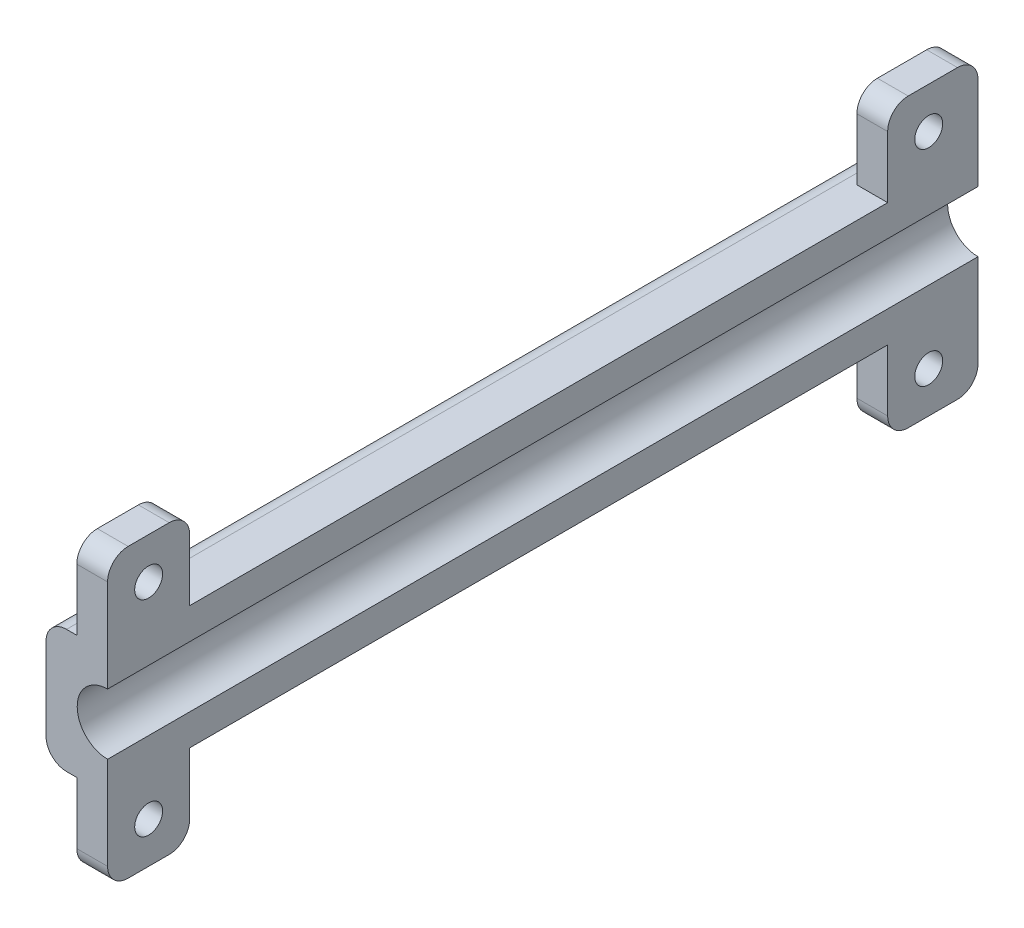
SolidWorks part; units mm, degrees
ref_plane "Front Plane" through (0, 0, 0) normal (0, 0, 1) x (1, 0, 0)
ref_plane "Top Plane" through (0, 0, 0) normal (0, 1, 0) x (1, 0, 0)
ref_plane "Right Plane" through (0, 0, 0) normal (1, 0, 0) x (0, 0, -1)
sketch "Sketch2" plane through (0, 0, 0) normal (0, 0, 1) x (1, 0, 0)
  line L0 (2.75, 15) -> (2.75, 0)
  line L1 (-4.75, 0) -> (10.25, 0)
  line L2 (-4.75, 0) -> (-4.75, 15)
  line L3 (-4.75, 15) -> (10.25, 15)
  line L4 (10.25, 0) -> (10.25, 15)
  line L5 (-4.75, 0) -> (10.25, 15) construction
  line L6 (-4.75, 15) -> (10.25, 0) construction
  circle A0 centre (2.75, 7.5) radius 3.7
  point P0 (2.75, 7.5)
  line M5 (2.75, 3.8) -> (2.75, -7.5)
  line M13 (2.75, 22.5) -> (2.75, 11.2)
extrude "Boss-Extrude1" add sketch "Sketch2" against normal up to surface (106 mm away) contours A0 L3 L2 L1 M13 M5
sketch "Sketch3" plane through (2.75, 0, 0) normal (-1, 0, 0) x (0, 0, 1)
  line L8 (-106, 3.8) -> (-106, -7.5)
  line L9 (-103.5, -10) -> (-97.5, -10)
  line L10 (-95, -7.5) -> (-95, 0)
  line L11 (-95, 0) -> (-10, 0)
  line L12 (-10, 0) -> (-10, -7.5)
  line L13 (-7.5, -10) -> (-2.5, -10)
  line L14 (0, -7.5) -> (0, 3.8)
  line L15 (0, 3.8) -> (-106, 3.8)
  line L17 (-103.5, -10) -> (-97.5, -10)
  line L18 (-95, -7.5) -> (-95, 0)
  line L19 (-95, 0) -> (-10, 0)
  line L20 (-10, 0) -> (-10, -7.5)
  line L21 (-7.5, -10) -> (-2.5, -10)
  line L22 (0, -7.5) -> (0, 3.8)
  line L23 (0, 3.8) -> (-106, 3.8)
  line L24 (-106, 11.2) -> (0, 11.2)
  line L25 (0, 11.2) -> (0, 22.5)
  line L26 (-2.5, 25) -> (-7.5, 25)
  line L27 (-10, 22.5) -> (-10, 15)
  line L28 (-10, 15) -> (-95, 15)
  line L29 (-95, 15) -> (-95, 22.5)
  line L30 (-97.5, 25) -> (-103.5, 25)
  line L31 (-106, 22.5) -> (-106, 11.2)
  line L32 (-106, 11.2) -> (0, 11.2)
  line L33 (0, 11.2) -> (0, 22.5)
  line L34 (-2.5, 25) -> (-7.5, 25)
  line L35 (-10, 22.5) -> (-10, 15)
  line L36 (-10, 15) -> (-95, 15)
  line L37 (-95, 15) -> (-95, 22.5)
  line L38 (-97.5, 25) -> (-103.5, 25)
  line L48 (-106, 3.8) -> (-106, -7.5)
  line L49 (-106, 22.5) -> (-106, 11.2)
  circle A0 centre (-100, 20) radius 1.7 construction
  circle A1 centre (-5, 20) radius 1.7 construction
  circle A2 centre (-5, -5) radius 1.7 construction
  circle A3 centre (-100, -5) radius 1.7 construction
  circle A4 centre (-5, 20) radius 1.7
  circle A5 centre (-5, -5) radius 1.7
  circle A6 centre (-100, -5) radius 1.7
  circle A7 centre (-100, 20) radius 1.7
  arc A16 (-106, -7.5) -> (-103.5, -10) centre (-103.5, -7.5) ccw
  arc A17 (-106, -7.5) -> (-103.5, -10) centre (-103.5, -7.5) ccw
  arc A18 (-97.5, -10) -> (-95, -7.5) centre (-97.5, -7.5) ccw
  arc A19 (-97.5, -10) -> (-95, -7.5) centre (-97.5, -7.5) ccw
  arc A20 (-10, -7.5) -> (-7.5, -10) centre (-7.5, -7.5) ccw
  arc A21 (-10, -7.5) -> (-7.5, -10) centre (-7.5, -7.5) ccw
  arc A22 (-2.5, -10) -> (0, -7.5) centre (-2.5, -7.5) ccw
  arc A23 (-2.5, -10) -> (0, -7.5) centre (-2.5, -7.5) ccw
  arc A24 (-103.5, 25) -> (-106, 22.5) centre (-103.5, 22.5) ccw
  arc A25 (-103.5, 25) -> (-106, 22.5) centre (-103.5, 22.5) ccw
  arc A26 (0, 22.5) -> (-2.5, 25) centre (-2.5, 22.5) ccw
  arc A27 (0, 22.5) -> (-2.5, 25) centre (-2.5, 22.5) ccw
  arc A28 (-7.5, 25) -> (-10, 22.5) centre (-7.5, 22.5) ccw
  arc A29 (-7.5, 25) -> (-10, 22.5) centre (-7.5, 22.5) ccw
  arc A30 (-95, 22.5) -> (-97.5, 25) centre (-97.5, 22.5) ccw
  arc A31 (-95, 22.5) -> (-97.5, 25) centre (-97.5, 22.5) ccw
  dimension "D1" = 0
  dimension "D2" = 0
extrude "Boss-Extrude2" add sketch "Sketch3" along normal blind 3.75
fillet "Fillet1" radius 2.5 2 edges at (-4.75, 0, -53) (-4.75, 15, -53)
